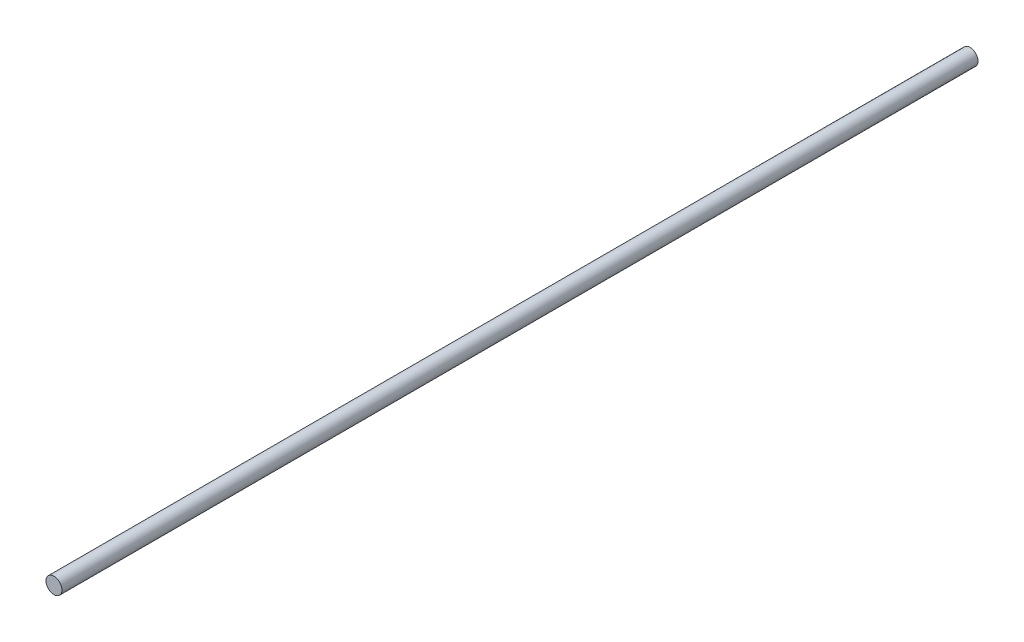
SolidWorks part; units mm, degrees
ref_plane "Front Plane" through (0, 0, 0) normal (0, 0, 1) x (1, 0, 0)
ref_plane "Top Plane" through (0, 0, 0) normal (0, 1, 0) x (1, 0, 0)
ref_plane "Right Plane" through (0, 0, 0) normal (1, 0, 0) x (0, 0, -1)
sketch "Sketch1" plane through (0, 0, 0) normal (0, 0, 1) x (1, 0, 0)
  circle A0 centre (0, 0) radius 3.5
extrude "Boss-Extrude1" add sketch "Sketch1" against normal blind 401
